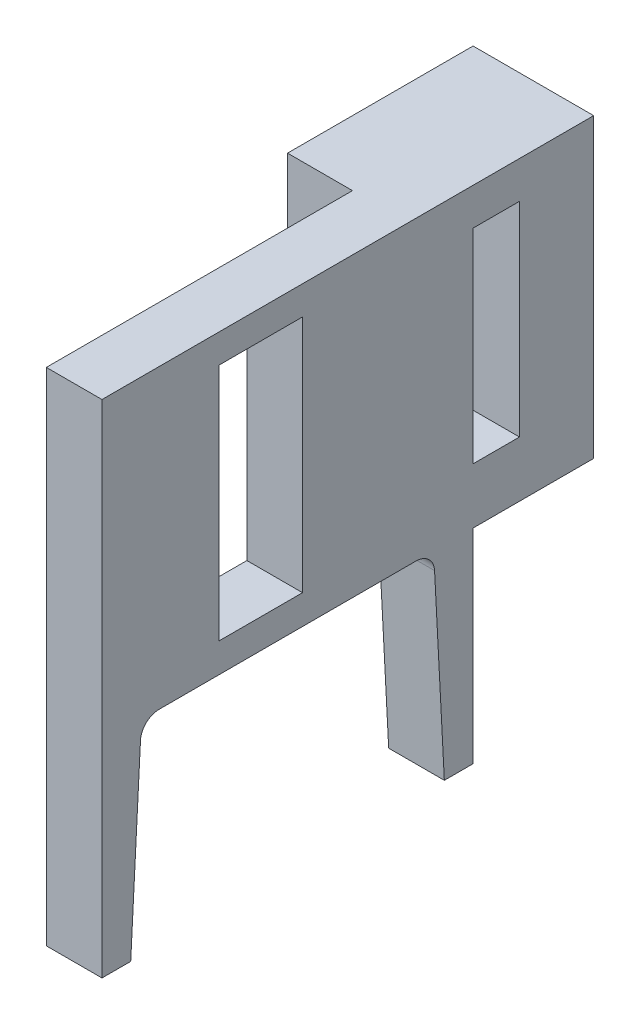
SolidWorks part; units mm, degrees
ref_plane "Front Plane" through (0, 0, 0) normal (0, 0, 1) x (1, 0, 0)
ref_plane "Top Plane" through (0, 0, 0) normal (0, 1, 0) x (1, 0, 0)
ref_plane "Right Plane" through (0, 0, 0) normal (1, 0, 0) x (0, 0, -1)
sketch "Sketch1" plane through (0, 0, 0) normal (1, 0, 0) x (0, 0, -1)
  line L1 (-26.5, 16) -> (26.5, 16)
  line L2 (-26.5, 16) -> (-26.5, -16)
  line L3 (-26.5, -16) -> (26.5, -16)
  line L4 (26.5, 16) -> (26.5, -16)
  line L5 (-26.5, 16) -> (26.5, -16) construction
  line L6 (-26.5, -16) -> (26.5, 16) construction
  point P0 (0, 0)
  dimension "D1" = 53
  dimension "D2" = 32
extrude "Boss-Extrude1" add sketch "Sketch1" along normal blind 13
sketch "Sketch7" plane through (0, 16, 0) normal (0, 1, 0) x (1, 0, 0)
  line L1 (0, 26.5) -> (7, 26.5)
  line L2 (0, 26.5) -> (0, -13.5)
  line L3 (0, -13.5) -> (7, -13.5)
  line L4 (7, 26.5) -> (7, -13.5)
  dimension "D1" = 40
  dimension "D2" = 7
extrude "Cut-Extrude3" cut sketch "Sketch7" against normal through all
sketch "Sketch19" plane through (0, -16, 0) normal (0, -1, 0) x (-1, 0, 0)
  line L0 (-7, -13.5) -> (-7, 26.5) construction
  line L1 (-13, 26.5) -> (-7, 26.5)
  line L2 (-13, 26.5) -> (-13, 22.25)
  line L3 (-13, 22.25) -> (-7, 22.25)
  line L4 (-7, 26.5) -> (-7, 22.25)
  line L5 (-13, -26.5) -> (-13, 26.5) construction
  line L6 (-7, -13.5) -> (-13, -13.5)
  line L7 (-7, -13.5) -> (-7, -9.25)
  line L8 (-7, -9.25) -> (-13, -9.25)
  line L9 (-13, -13.5) -> (-13, -9.25)
  dimension "D1" = 4.25
  dimension "D2" = 4.25
sketch "Sketch8" plane through (0, -16, 0) normal (0, -1, 0) x (1, 0, 0)
  line L1 (13, -26.5) -> (7, -26.5)
  line L2 (13, -26.5) -> (13, 13.5)
  line L3 (13, 13.5) -> (7, 13.5)
  line L4 (7, -26.5) -> (7, 13.5)
extrude "Boss-Extrude2" add sketch "Sketch8" along normal blind 22
sketch "Sketch20" plane through (0, -16, 0) normal (0, -1, 0) x (-1, 0, 0)
  line L1 (-13, -9.25) -> (-7, -9.25)
  line L2 (-13, -9.25) -> (-13, 22.25)
  line L3 (-13, 22.25) -> (-7, 22.25)
  line L4 (-7, -9.25) -> (-7, 22.25)
extrude "Cut-Extrude9" cut sketch "Sketch20" along normal through all draft 3 draft outward yes
fillet "Fillet1" radius 2 1 edges at (10, -16, -22.25)
fillet "Fillet2" radius 2 1 edges at (10, -16, 9.25)
sketch "Sketch49" plane through (0, 0, 13.5) normal (0, 0, -1) x (-1, 0, 0)
  line L1 (-7, -16) -> (0, -16)
  line L2 (-7, -16) -> (-7, 16)
  line L3 (-7, 16) -> (0, 16)
  line L4 (0, -16) -> (0, 16)
extrude "Boss-Extrude3" add sketch "Sketch49" along normal blind 7
sketch "Sketch50" plane through (0, -16, 0) normal (0, -1, 0) x (1, 0, 0)
  line L1 (7, 6.5) -> (0, 6.5)
  line L2 (7, 6.5) -> (7, 26.5)
  line L3 (7, 26.5) -> (0, 26.5)
  line L4 (0, 6.5) -> (0, 26.5)
extrude "Cut-Extrude19" cut sketch "Sketch50" against normal blind 3
sketch "Sketch35" plane through (7, 0, 0) normal (-1, 0, 0) x (0, 0, 1)
  line L1 (-13.8814, 12.9016) -> (-4.8814, 12.9016)
  line L2 (-13.8814, 12.9016) -> (-13.8814, -12.8405)
  line L3 (-13.8814, -12.8405) -> (-4.8814, -12.8405)
  line L4 (-4.8814, 12.9016) -> (-4.8814, -12.8405)
  dimension "D1" = 9
extrude "Cut-Extrude15" cut sketch "Sketch35" against normal through all
sketch "Sketch36" plane through (7, 0, 0) normal (-1, 0, 0) x (0, 0, 1)
  line L1 (-3.6189, 12.6982) -> (4.8929, 12.6982)
  line L2 (-3.6189, 12.6982) -> (-3.6189, -13)
  line L3 (-3.6189, -13) -> (4.8929, -13)
  line L4 (4.8929, 12.6982) -> (4.8929, -13)
extrude "Cut-Extrude16" cut sketch "Sketch36" against normal blind 5
sketch "Sketch51" plane through (7, 0, 0) normal (-1, 0, 0) x (0, 0, 1)
  line L0 (7.3521, -16) -> (-20.3521, -16) construction
  line L1 (-26.5, 16) -> (-24.5, 16)
  line L2 (-26.5, 16) -> (-26.5, -16)
  line L3 (-26.5, -16) -> (-24.5, -16)
  line L4 (-24.5, 16) -> (-24.5, -16)
  dimension "D1" = 2
sketch "Sketch52" plane through (7, 0, 0) normal (-1, 0, 0) x (0, 0, 1)
  line L0 (7.3521, -16) -> (-20.3521, -16) construction
  line L1 (-13.8814, 12.9016) -> (-15.8814, 12.9016)
  line L2 (-13.8814, 12.9016) -> (-13.8814, -16)
  line L3 (-13.8814, -16) -> (-15.8814, -16)
  line L4 (-15.8814, 12.9016) -> (-15.8814, -16)
  dimension "D1" = 2
sketch "Sketch54" plane through (7, 0, 0) normal (-1, 0, 0) x (0, 0, 1)
  line L1 (4.8929, -13) -> (-26.5, -13)
  line L2 (4.8929, -13) -> (4.8929, -16)
  line L3 (4.8929, -16) -> (-26.5, -16)
  line L4 (-26.5, -13) -> (-26.5, -16)
sketch "Sketch55" plane through (7, 0, 0) normal (-1, 0, 0) x (0, 0, 1)
  line L1 (-15.8814, 12.9016) -> (-24.5316, 12.9016)
  line L2 (-15.8814, 12.9016) -> (-15.8814, -13.1088)
  line L3 (-15.8814, -13.1088) -> (-24.5316, -13.1088)
  line L4 (-24.5316, 12.9016) -> (-24.5316, -13.1088)
extrude "Cut-Extrude20" cut sketch "Sketch55" against normal blind 5
sketch "Sketch56" plane through (0, 0, 0) normal (-1, 0, 0) x (0, 0, 1)
  line L1 (6.5, 16) -> (13.5, 16)
  line L2 (6.5, 16) -> (6.5, -13)
  line L3 (6.5, -13) -> (13.5, -13)
  line L4 (13.5, 16) -> (13.5, -13)
  point P5 (0, 0)
  dimension "D1" = 7
sketch "Sketch61" plane through (0, 0, 0) normal (-1, 0, 0) x (0, 0, 1)
  line L1 (13.5, -13) -> (26.5, -13)
  line L2 (13.5, -13) -> (13.5, -10)
  line L3 (13.5, -10) -> (26.5, -10)
  line L4 (26.5, -13) -> (26.5, -10)
  dimension "D1" = 13
  dimension "D2" = 3
sketch "Sketch62" plane through (0, 0, 0) normal (-1, 0, 0) x (0, 0, 1)
  line L0 (26.5, 16) -> (26.5, -13) construction
  line L1 (13.5, 16) -> (26.5, 16)
  line L2 (13.5, 16) -> (13.5, 12)
  line L3 (13.5, 12) -> (26.5, 12)
  line L4 (26.5, 16) -> (26.5, 12)
  dimension "D1" = 4
sketch "Sketch63" plane through (0, 0, 0) normal (-1, 0, 0) x (0, 0, 1)
  line L1 (13.5, 12) -> (18.5, 12)
  line L2 (13.5, 12) -> (13.5, -10)
  line L3 (13.5, -10) -> (18.5, -10)
  line L4 (18.5, 12) -> (18.5, -10)
  dimension "D1" = 5
  dimension "D2" = 22
extrude "Cut-Extrude21" cut sketch "Sketch63" against normal through all
mirror "Mirror1" about plane through (13, 16, 26.5) normal (0, 0, -1) of bodies 124
delete or keep bodies "Body-Delete/Keep 1" type delete bodies bodies 124
